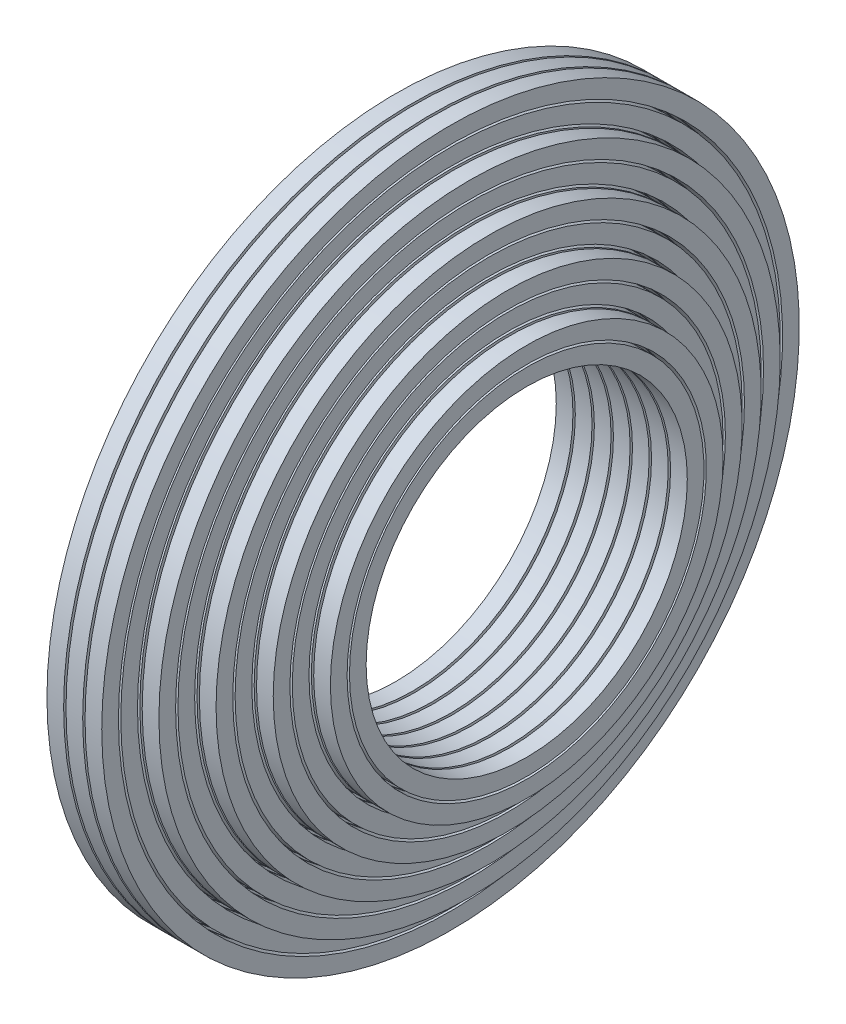
SolidWorks part; units mm, degrees
ref_plane "Front Plane" through (0, 0, 0) normal (0, 0, 1) x (1, 0, 0)
ref_plane "Top Plane" through (0, 0, 0) normal (0, 1, 0) x (1, 0, 0)
ref_plane "Right Plane" through (0, 0, 0) normal (1, 0, 0) x (0, 0, -1)
sketch "Sketch1" plane through (0, 0, 0) normal (0, 0, 1) x (1, 0, 0)
  line L0 (0, 0) -> (17.4911, 0) construction
  line L1 (9.773, 36.1) -> (13.173, 36.1)
  line L2 (5.893, 32.7) -> (9.293, 32.7)
  line L3 (5.893, 32.7) -> (5.893, 36.1)
  line L4 (5.893, 36.1) -> (9.293, 36.1)
  line L5 (9.293, 32.7) -> (9.293, 36.1)
  line L6 (9.773, 32.7) -> (9.773, 36.1)
  line L7 (9.773, 32.7) -> (13.173, 32.7)
  line L8 (13.173, 32.7) -> (13.173, 36.1)
  line L9 (13.653, 36.1) -> (17.053, 36.1)
  line L10 (13.653, 32.7) -> (13.653, 36.1)
  line L11 (13.653, 32.7) -> (17.053, 32.7)
  line L12 (17.053, 32.7) -> (17.053, 36.1)
  line L13 (17.533, 36.1) -> (20.933, 36.1)
  line L14 (17.533, 32.7) -> (17.533, 36.1)
  line L15 (17.533, 32.7) -> (20.933, 32.7)
  line L16 (20.933, 32.7) -> (20.933, 36.1)
  line L17 (21.413, 36.1) -> (24.813, 36.1)
  line L18 (21.413, 32.7) -> (21.413, 36.1)
  line L19 (21.413, 32.7) -> (24.813, 32.7)
  line L20 (24.813, 32.7) -> (24.813, 36.1)
  line L21 (25.293, 36.1) -> (28.693, 36.1)
  line L22 (25.293, 32.7) -> (25.293, 36.1)
  line L23 (25.293, 32.7) -> (28.693, 32.7)
  line L24 (28.693, 32.7) -> (28.693, 36.1)
  line L25 (29.173, 36.1) -> (32.573, 36.1)
  line L26 (29.173, 32.7) -> (29.173, 36.1)
  line L27 (29.173, 32.7) -> (32.573, 32.7)
  line L28 (32.573, 32.7) -> (32.573, 36.1)
  line L29 (5.893, 39.98) -> (9.293, 39.98)
  line L30 (5.893, 36.58) -> (5.893, 39.98)
  line L31 (5.893, 36.58) -> (9.293, 36.58)
  line L32 (9.293, 36.58) -> (9.293, 39.98)
  line L33 (9.773, 39.98) -> (13.173, 39.98)
  line L34 (9.773, 36.58) -> (9.773, 39.98)
  line L35 (9.773, 36.58) -> (13.173, 36.58)
  line L36 (13.173, 36.58) -> (13.173, 39.98)
  line L37 (13.653, 39.98) -> (17.053, 39.98)
  line L38 (13.653, 36.58) -> (13.653, 39.98)
  line L39 (13.653, 36.58) -> (17.053, 36.58)
  line L40 (17.053, 36.58) -> (17.053, 39.98)
  line L41 (17.533, 39.98) -> (20.933, 39.98)
  line L42 (17.533, 36.58) -> (17.533, 39.98)
  line L43 (17.533, 36.58) -> (20.933, 36.58)
  line L44 (20.933, 36.58) -> (20.933, 39.98)
  line L45 (21.413, 39.98) -> (24.813, 39.98)
  line L46 (21.413, 36.58) -> (21.413, 39.98)
  line L47 (21.413, 36.58) -> (24.813, 36.58)
  line L48 (24.813, 36.58) -> (24.813, 39.98)
  line L49 (25.293, 39.98) -> (28.693, 39.98)
  line L50 (25.293, 36.58) -> (25.293, 39.98)
  line L51 (25.293, 36.58) -> (28.693, 36.58)
  line L52 (28.693, 36.58) -> (28.693, 39.98)
  line L53 (29.173, 39.98) -> (32.573, 39.98)
  line L54 (29.173, 36.58) -> (29.173, 39.98)
  line L55 (29.173, 36.58) -> (32.573, 36.58)
  line L56 (32.573, 36.58) -> (32.573, 39.98)
  line L57 (5.893, 43.86) -> (9.293, 43.86)
  line L58 (5.893, 40.46) -> (5.893, 43.86)
  line L59 (5.893, 40.46) -> (9.293, 40.46)
  line L60 (9.293, 40.46) -> (9.293, 43.86)
  line L61 (9.773, 43.86) -> (13.173, 43.86)
  line L62 (9.773, 40.46) -> (9.773, 43.86)
  line L63 (9.773, 40.46) -> (13.173, 40.46)
  line L64 (13.173, 40.46) -> (13.173, 43.86)
  line L65 (13.653, 43.86) -> (17.053, 43.86)
  line L66 (13.653, 40.46) -> (13.653, 43.86)
  line L67 (13.653, 40.46) -> (17.053, 40.46)
  line L68 (17.053, 40.46) -> (17.053, 43.86)
  line L69 (17.533, 43.86) -> (20.933, 43.86)
  line L70 (17.533, 40.46) -> (17.533, 43.86)
  line L71 (17.533, 40.46) -> (20.933, 40.46)
  line L72 (20.933, 40.46) -> (20.933, 43.86)
  line L73 (21.413, 43.86) -> (24.813, 43.86)
  line L74 (21.413, 40.46) -> (21.413, 43.86)
  line L75 (21.413, 40.46) -> (24.813, 40.46)
  line L76 (24.813, 40.46) -> (24.813, 43.86)
  line L77 (25.293, 43.86) -> (28.693, 43.86)
  line L78 (25.293, 40.46) -> (25.293, 43.86)
  line L79 (25.293, 40.46) -> (28.693, 40.46)
  line L80 (28.693, 40.46) -> (28.693, 43.86)
  line L85 (5.893, 47.74) -> (9.293, 47.74)
  line L86 (5.893, 44.34) -> (5.893, 47.74)
  line L87 (5.893, 44.34) -> (9.293, 44.34)
  line L88 (9.293, 44.34) -> (9.293, 47.74)
  line L89 (9.773, 47.74) -> (13.173, 47.74)
  line L90 (9.773, 44.34) -> (9.773, 47.74)
  line L91 (9.773, 44.34) -> (13.173, 44.34)
  line L92 (13.173, 44.34) -> (13.173, 47.74)
  line L93 (13.653, 47.74) -> (17.053, 47.74)
  line L94 (13.653, 44.34) -> (13.653, 47.74)
  line L95 (13.653, 44.34) -> (17.053, 44.34)
  line L96 (17.053, 44.34) -> (17.053, 47.74)
  line L97 (17.533, 47.74) -> (20.933, 47.74)
  line L98 (17.533, 44.34) -> (17.533, 47.74)
  line L99 (17.533, 44.34) -> (20.933, 44.34)
  line L100 (20.933, 44.34) -> (20.933, 47.74)
  line L101 (21.413, 47.74) -> (24.813, 47.74)
  line L102 (21.413, 44.34) -> (21.413, 47.74)
  line L103 (21.413, 44.34) -> (24.813, 44.34)
  line L104 (24.813, 44.34) -> (24.813, 47.74)
  line L105 (25.293, 47.74) -> (28.693, 47.74)
  line L106 (25.293, 44.34) -> (25.293, 47.74)
  line L107 (25.293, 44.34) -> (28.693, 44.34)
  line L108 (28.693, 44.34) -> (28.693, 47.74)
  line L113 (5.893, 51.62) -> (9.293, 51.62)
  line L114 (5.893, 48.22) -> (5.893, 51.62)
  line L115 (5.893, 48.22) -> (9.293, 48.22)
  line L116 (9.293, 48.22) -> (9.293, 51.62)
  line L117 (9.773, 51.62) -> (13.173, 51.62)
  line L118 (9.773, 48.22) -> (9.773, 51.62)
  line L119 (9.773, 48.22) -> (13.173, 48.22)
  line L120 (13.173, 48.22) -> (13.173, 51.62)
  line L121 (13.653, 51.62) -> (17.053, 51.62)
  line L122 (13.653, 48.22) -> (13.653, 51.62)
  line L123 (13.653, 48.22) -> (17.053, 48.22)
  line L124 (17.053, 48.22) -> (17.053, 51.62)
  line L125 (17.533, 51.62) -> (20.933, 51.62)
  line L126 (17.533, 48.22) -> (17.533, 51.62)
  line L127 (17.533, 48.22) -> (20.933, 48.22)
  line L128 (20.933, 48.22) -> (20.933, 51.62)
  line L129 (21.413, 51.62) -> (24.813, 51.62)
  line L130 (21.413, 48.22) -> (21.413, 51.62)
  line L131 (21.413, 48.22) -> (24.813, 48.22)
  line L132 (24.813, 48.22) -> (24.813, 51.62)
  line L141 (5.893, 55.5) -> (9.293, 55.5)
  line L142 (5.893, 52.1) -> (5.893, 55.5)
  line L143 (5.893, 52.1) -> (9.293, 52.1)
  line L144 (9.293, 52.1) -> (9.293, 55.5)
  line L145 (9.773, 55.5) -> (13.173, 55.5)
  line L146 (9.773, 52.1) -> (9.773, 55.5)
  line L147 (9.773, 52.1) -> (13.173, 52.1)
  line L148 (13.173, 52.1) -> (13.173, 55.5)
  line L149 (13.653, 55.5) -> (17.053, 55.5)
  line L150 (13.653, 52.1) -> (13.653, 55.5)
  line L151 (13.653, 52.1) -> (17.053, 52.1)
  line L152 (17.053, 52.1) -> (17.053, 55.5)
  line L153 (17.533, 55.5) -> (20.933, 55.5)
  line L154 (17.533, 52.1) -> (17.533, 55.5)
  line L155 (17.533, 52.1) -> (20.933, 52.1)
  line L156 (20.933, 52.1) -> (20.933, 55.5)
  line L157 (21.413, 55.5) -> (24.813, 55.5)
  line L158 (21.413, 52.1) -> (21.413, 55.5)
  line L159 (21.413, 52.1) -> (24.813, 52.1)
  line L160 (24.813, 52.1) -> (24.813, 55.5)
  line L169 (5.893, 59.38) -> (9.293, 59.38)
  line L170 (5.893, 55.98) -> (5.893, 59.38)
  line L171 (5.893, 55.98) -> (9.293, 55.98)
  line L172 (9.293, 55.98) -> (9.293, 59.38)
  line L173 (9.773, 59.38) -> (13.173, 59.38)
  line L174 (9.773, 55.98) -> (9.773, 59.38)
  line L175 (9.773, 55.98) -> (13.173, 55.98)
  line L176 (13.173, 55.98) -> (13.173, 59.38)
  line L177 (13.653, 59.38) -> (17.053, 59.38)
  line L178 (13.653, 55.98) -> (13.653, 59.38)
  line L179 (13.653, 55.98) -> (17.053, 55.98)
  line L180 (17.053, 55.98) -> (17.053, 59.38)
  line L181 (17.533, 59.38) -> (20.933, 59.38)
  line L182 (17.533, 55.98) -> (17.533, 59.38)
  line L183 (17.533, 55.98) -> (20.933, 55.98)
  line L184 (20.933, 55.98) -> (20.933, 59.38)
  line L197 (5.893, 63.26) -> (9.293, 63.26)
  line L198 (5.893, 59.86) -> (5.893, 63.26)
  line L199 (5.893, 59.86) -> (9.293, 59.86)
  line L200 (9.293, 59.86) -> (9.293, 63.26)
  line L201 (9.773, 63.26) -> (13.173, 63.26)
  line L202 (9.773, 59.86) -> (9.773, 63.26)
  line L203 (9.773, 59.86) -> (13.173, 59.86)
  line L204 (13.173, 59.86) -> (13.173, 63.26)
  line L205 (13.653, 63.26) -> (17.053, 63.26)
  line L206 (13.653, 59.86) -> (13.653, 63.26)
  line L207 (13.653, 59.86) -> (17.053, 59.86)
  line L208 (17.053, 59.86) -> (17.053, 63.26)
  line L209 (17.533, 63.26) -> (20.933, 63.26)
  line L210 (17.533, 59.86) -> (17.533, 63.26)
  line L211 (17.533, 59.86) -> (20.933, 59.86)
  line L212 (20.933, 59.86) -> (20.933, 63.26)
  line L225 (5.893, 67.14) -> (9.293, 67.14)
  line L226 (5.893, 63.74) -> (5.893, 67.14)
  line L227 (5.893, 63.74) -> (9.293, 63.74)
  line L228 (9.293, 63.74) -> (9.293, 67.14)
  line L229 (9.773, 67.14) -> (13.173, 67.14)
  line L230 (9.773, 63.74) -> (9.773, 67.14)
  line L231 (9.773, 63.74) -> (13.173, 63.74)
  line L232 (13.173, 63.74) -> (13.173, 67.14)
  line L233 (13.653, 67.14) -> (17.053, 67.14)
  line L234 (13.653, 63.74) -> (13.653, 67.14)
  line L235 (13.653, 63.74) -> (17.053, 63.74)
  line L236 (17.053, 63.74) -> (17.053, 67.14)
  line L253 (5.893, 71.02) -> (9.293, 71.02)
  line L254 (5.893, 67.62) -> (5.893, 71.02)
  line L255 (5.893, 67.62) -> (9.293, 67.62)
  line L256 (9.293, 67.62) -> (9.293, 71.02)
  line L257 (9.773, 71.02) -> (13.173, 71.02)
  line L258 (9.773, 67.62) -> (9.773, 71.02)
  line L259 (9.773, 67.62) -> (13.173, 67.62)
  line L260 (13.173, 67.62) -> (13.173, 71.02)
  line L261 (13.653, 71.02) -> (17.053, 71.02)
  line L262 (13.653, 67.62) -> (13.653, 71.02)
  line L263 (13.653, 67.62) -> (17.053, 67.62)
  line L264 (17.053, 67.62) -> (17.053, 71.02)
  line L281 (29.173, 43.86) -> (32.573, 43.86) [skipped]
  line L282 (29.173, 40.46) -> (29.173, 43.86) [skipped]
  line L283 (29.173, 40.46) -> (32.573, 40.46) [skipped]
  line L284 (32.573, 40.46) -> (32.573, 43.86) [skipped]
  line L285 (29.173, 47.74) -> (32.573, 47.74) [skipped]
  line L286 (29.173, 44.34) -> (29.173, 47.74) [skipped]
  line L287 (29.173, 44.34) -> (32.573, 44.34) [skipped]
  line L288 (32.573, 44.34) -> (32.573, 47.74) [skipped]
  line L289 (29.173, 51.62) -> (32.573, 51.62) [skipped]
  line L290 (29.173, 48.22) -> (29.173, 51.62) [skipped]
  line L291 (29.173, 48.22) -> (32.573, 48.22) [skipped]
  line L292 (32.573, 48.22) -> (32.573, 51.62) [skipped]
  line L293 (29.173, 55.5) -> (32.573, 55.5) [skipped]
  line L294 (29.173, 52.1) -> (29.173, 55.5) [skipped]
  line L295 (29.173, 52.1) -> (32.573, 52.1) [skipped]
  line L296 (32.573, 52.1) -> (32.573, 55.5) [skipped]
  line L297 (29.173, 59.38) -> (32.573, 59.38) [skipped]
  line L298 (29.173, 55.98) -> (29.173, 59.38) [skipped]
  line L299 (29.173, 55.98) -> (32.573, 55.98) [skipped]
  line L300 (32.573, 55.98) -> (32.573, 59.38) [skipped]
  line L301 (29.173, 63.26) -> (32.573, 63.26) [skipped]
  line L302 (29.173, 59.86) -> (29.173, 63.26) [skipped]
  line L303 (29.173, 59.86) -> (32.573, 59.86) [skipped]
  line L304 (32.573, 59.86) -> (32.573, 63.26) [skipped]
  line L305 (29.173, 67.14) -> (32.573, 67.14) [skipped]
  line L306 (29.173, 63.74) -> (29.173, 67.14) [skipped]
  line L307 (29.173, 63.74) -> (32.573, 63.74) [skipped]
  line L308 (32.573, 63.74) -> (32.573, 67.14) [skipped]
  line L309 (29.173, 71.02) -> (32.573, 71.02) [skipped]
  line L310 (29.173, 67.62) -> (29.173, 71.02) [skipped]
  line L311 (29.173, 67.62) -> (32.573, 67.62) [skipped]
  line L312 (32.573, 67.62) -> (32.573, 71.02) [skipped]
  line L313 (25.293, 51.62) -> (28.693, 51.62) [skipped]
  line L314 (25.293, 48.22) -> (25.293, 51.62) [skipped]
  line L315 (25.293, 48.22) -> (28.693, 48.22) [skipped]
  line L316 (28.693, 48.22) -> (28.693, 51.62) [skipped]
  line L317 (25.293, 55.5) -> (28.693, 55.5) [skipped]
  line L318 (25.293, 52.1) -> (25.293, 55.5) [skipped]
  line L319 (25.293, 52.1) -> (28.693, 52.1) [skipped]
  line L320 (28.693, 52.1) -> (28.693, 55.5) [skipped]
  line L321 (25.293, 59.38) -> (28.693, 59.38) [skipped]
  line L322 (25.293, 55.98) -> (25.293, 59.38) [skipped]
  line L323 (25.293, 55.98) -> (28.693, 55.98) [skipped]
  line L324 (28.693, 55.98) -> (28.693, 59.38) [skipped]
  line L325 (25.293, 63.26) -> (28.693, 63.26) [skipped]
  line L326 (25.293, 59.86) -> (25.293, 63.26) [skipped]
  line L327 (25.293, 59.86) -> (28.693, 59.86) [skipped]
  line L328 (28.693, 59.86) -> (28.693, 63.26) [skipped]
  line L329 (25.293, 67.14) -> (28.693, 67.14) [skipped]
  line L330 (25.293, 63.74) -> (25.293, 67.14) [skipped]
  line L331 (25.293, 63.74) -> (28.693, 63.74) [skipped]
  line L332 (28.693, 63.74) -> (28.693, 67.14) [skipped]
  line L333 (25.293, 71.02) -> (28.693, 71.02) [skipped]
  line L334 (25.293, 67.62) -> (25.293, 71.02) [skipped]
  line L335 (25.293, 67.62) -> (28.693, 67.62) [skipped]
  line L336 (28.693, 67.62) -> (28.693, 71.02) [skipped]
  line L337 (21.413, 59.38) -> (24.813, 59.38) [skipped]
  line L338 (21.413, 55.98) -> (21.413, 59.38) [skipped]
  line L339 (21.413, 55.98) -> (24.813, 55.98) [skipped]
  line L340 (24.813, 55.98) -> (24.813, 59.38) [skipped]
  line L341 (21.413, 63.26) -> (24.813, 63.26) [skipped]
  line L342 (21.413, 59.86) -> (21.413, 63.26) [skipped]
  line L343 (21.413, 59.86) -> (24.813, 59.86) [skipped]
  line L344 (24.813, 59.86) -> (24.813, 63.26) [skipped]
  line L345 (21.413, 67.14) -> (24.813, 67.14) [skipped]
  line L346 (21.413, 63.74) -> (21.413, 67.14) [skipped]
  line L347 (21.413, 63.74) -> (24.813, 63.74) [skipped]
  line L348 (24.813, 63.74) -> (24.813, 67.14) [skipped]
  line L349 (21.413, 71.02) -> (24.813, 71.02) [skipped]
  line L350 (21.413, 67.62) -> (21.413, 71.02) [skipped]
  line L351 (21.413, 67.62) -> (24.813, 67.62) [skipped]
  line L352 (24.813, 67.62) -> (24.813, 71.02) [skipped]
  line L353 (17.533, 67.14) -> (20.933, 67.14) [skipped]
  line L354 (17.533, 63.74) -> (17.533, 67.14) [skipped]
  line L355 (17.533, 63.74) -> (20.933, 63.74) [skipped]
  line L356 (20.933, 63.74) -> (20.933, 67.14) [skipped]
  line L357 (17.533, 71.02) -> (20.933, 71.02) [skipped]
  line L358 (17.533, 67.62) -> (17.533, 71.02) [skipped]
  line L359 (17.533, 67.62) -> (20.933, 67.62) [skipped]
  line L360 (20.933, 67.62) -> (20.933, 71.02) [skipped]
  dimension "D1" = 3.4
  dimension "D2" = 65.4
  dimension "D3" = 7
  dimension "D4" = 10
revolve "Revolve2" add sketch "Sketch1" angle 360 about L0
